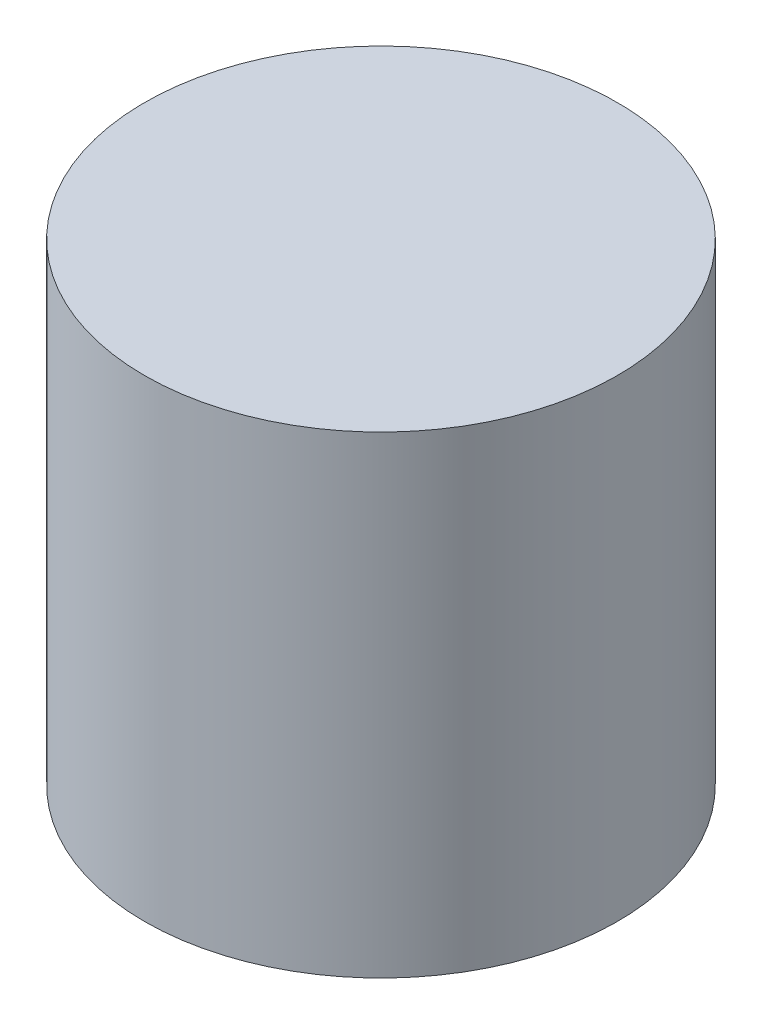
SolidWorks part; units mm, degrees
ref_plane "Front Plane" through (0, 0, 0) normal (0, 0, 1) x (1, 0, 0)
ref_plane "Top Plane" through (0, 0, 0) normal (0, 1, 0) x (1, 0, 0)
ref_plane "Right Plane" through (0, 0, 0) normal (1, 0, 0) x (0, 0, -1)
sketch "Sketch1" plane through (0, 0, 0) normal (0, 1, 0) x (1, 0, 0)
  circle A0 centre (0, 0) radius 4
extrude "Boss-Extrude1" add sketch "Sketch1" along normal blind 8
